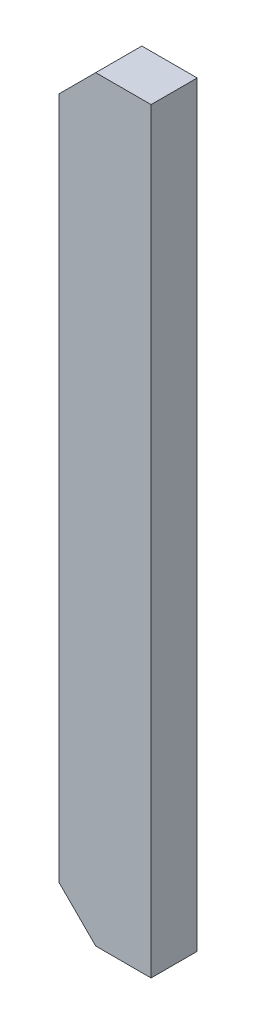
SolidWorks part; units mm, degrees
ref_plane "前视基准面" through (0, 0, 0) normal (0, 0, 1) x (1, 0, 0)
ref_plane "上视基准面" through (0, 0, 0) normal (0, 1, 0) x (1, 0, 0)
ref_plane "右视基准面" through (0, 0, 0) normal (1, 0, 0) x (0, 0, -1)
sketch "草图1" plane through (0, 0, 0) normal (0, 0, 1) x (1, 0, 0)
  line L0 (0, 0) -> (-12, 0)
  line L1 (-12, 0) -> (-20, -8)
  line L2 (-20, -8) -> (-20, -156)
  line L3 (-20, -156) -> (-12, -164)
  line L4 (-12, -164) -> (0, -164)
  line L5 (0, -164) -> (0, 0)
  point P3 (-8.4352, 0)
  point P8 (-20, -12.7476)
  point P9 (-10.7519, -164)
  dimension "D1" = 164
  dimension "D2" = 20
  dimension "D3" = 12
  dimension "D4" = 45
  dimension "D5" = 12
  dimension "D6" = 45
extrude "凸台-拉伸1" add sketch "草图1" along normal blind 10
